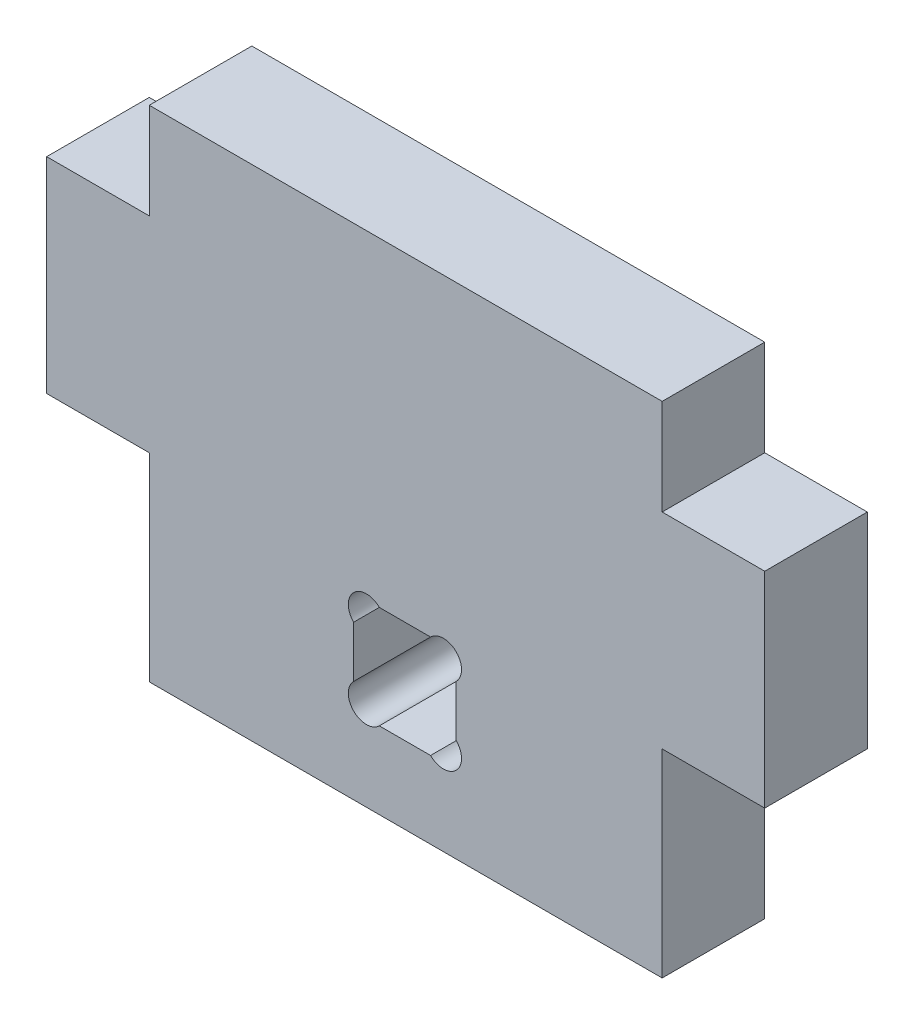
SolidWorks part; units mm, degrees
material "6061 Alloy"
ref_plane "Front" through (0, 0, 0) normal (0, 0, 1) x (1, 0, 0)
ref_plane "Top" through (0, 0, 0) normal (0, 1, 0) x (1, 0, 0)
ref_plane "Right" through (0, 0, 0) normal (1, 0, 0) x (0, 0, -1)
sketch "Sketch1" plane through (0, 0, 0) normal (0, 0, 1) x (1, 0, 0)
  line L0 (-32.1632, -6.0401) -> (-32.1632, -30.604)
  line L1 (-44.8632, 19.3599) -> (-32.1632, 19.3599)
  line L2 (-44.8632, 19.3599) -> (-44.8632, -6.0401)
  line L3 (-44.8632, -6.0401) -> (-32.1632, -6.0401)
  line L4 (44.0368, 19.3599) -> (31.3368, 19.3599)
  line L5 (44.0368, 19.3599) -> (44.0368, -6.0401)
  line L6 (44.0368, -6.0401) -> (31.3368, -6.0401)
  line L7 (-32.1632, 31.2238) -> (31.3368, 31.2238)
  line L8 (-32.1632, 31.2238) -> (-32.1632, 19.3599)
  line L9 (-32.1632, -30.604) -> (31.3368, -30.604)
  line L10 (31.3368, 31.2238) -> (31.3368, 19.3599)
  line L11 (31.3368, -6.0401) -> (31.3368, -30.604)
extrude "Boss-Extrude1" add sketch "Sketch1" along normal blind 12.7
sketch "Sketch2" plane through (0, 0, 12.7) normal (0, 0, 1) x (1, 0, 0)
  line L0 (-13.1132, -14.729) -> (12.0909, -14.729) construction
  line L1 (-0.5111, -14.729) -> (-0.5111, -30.604) construction
  line L2 (-6.8611, -21.079) -> (5.8389, -21.079)
  line L3 (-6.8611, -21.079) -> (-6.8611, -8.379)
  line L4 (-6.8611, -8.379) -> (5.8389, -8.379)
  line L5 (5.8389, -21.079) -> (5.8389, -8.379)
  line L6 (-6.8611, -21.079) -> (5.8389, -8.379) construction
  line L7 (-6.8611, -8.379) -> (5.8389, -21.079) construction
  circle A1 centre (-5.2736, -9.9665) radius 2.2454
  circle A2 centre (-5.2736, -19.4915) radius 2.2454
  circle A3 centre (4.2514, -19.4915) radius 2.2454
  circle A4 centre (4.2514, -9.9665) radius 2.2454
  point P0 (-0.5111, -14.729)
  dimension "D5" = 1.5875
  dimension "D3" = 4.4907
  dimension "D1" = 12.7
  dimension "D2" = 12.7
  dimension "D4" = 1.5875
extrude "Cut-Extrude1" cut sketch "Sketch2" against normal through all contours A1 | A4 | A2 | A3 | L2 L5 L4 L3
